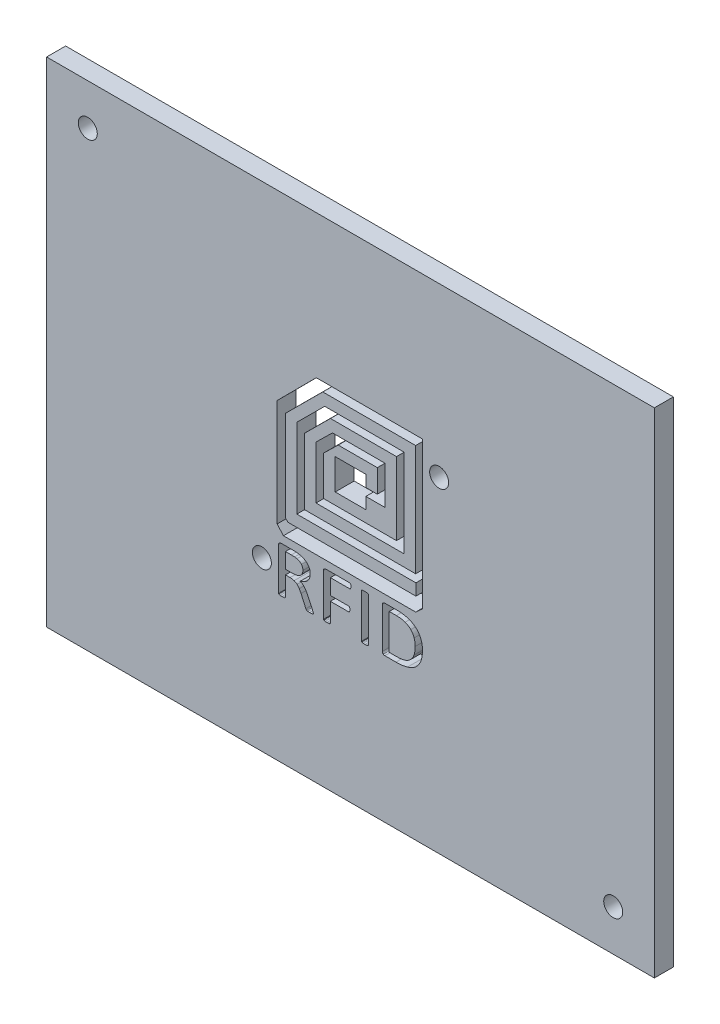
SolidWorks part; units mm, degrees
ref_plane "Alzado" through (0, 0, 0) normal (0, 0, 1) x (1, 0, 0)
ref_plane "Planta" through (0, 0, 0) normal (0, 1, 0) x (1, 0, 0)
ref_plane "Vista lateral" through (0, 0, 0) normal (1, 0, 0) x (0, 0, -1)
sketch "Croquis1" plane through (0, 0, 0) normal (0, 0, 1) x (1, 0, 0)
  line L5 (-48, -39) -> (48, -39)
  line L6 (-48, -39) -> (-48, 39)
  line L19 (-48, 39) -> (48, 39)
  line L24 (48, -39) -> (48, 39)
  line L25 (-48, -39) -> (48, 39) construction
  line L26 (-48, 39) -> (48, -39) construction
  point P0 (0, 0)
  dimension "D1" = 96
  dimension "D2" = 78
extrude "Saliente-Extruir2" add sketch "Croquis1" against normal blind 3
sketch "Croquis2" plane through (0, 0, 0) normal (0, 0, 1) x (1, 0, 0)
  line L0 (0, 39) -> (0, -39) construction
  line L1 (-21.5, 20) -> (21.5, 20) construction
  line L2 (-21.5, 20) -> (-21.5, -20) construction
  line L3 (-21.5, -20) -> (21.5, -20) construction
  line L4 (21.5, 20) -> (21.5, -20) construction
  line L5 (-48, 39) -> (48, 39) construction
  line L6 (0, 20) -> (0, -20) construction
  line L15 (-21.5, 0) -> (21.5, 0) construction
  line L16 (-48, -39) -> (48, -39) construction
  line L17 (-48, 0) -> (48, 0) construction
  line L18 (-48, -39) -> (-48, 39) construction
  line L20 (-48, 39) -> (48, 39)
  line L21 (48, -39) -> (48, 39) construction
  line L22 (-48, 39) -> (-48, -39)
  line L23 (-48, -39) -> (48, -39)
  line L24 (48, 39) -> (48, -39)
  circle A1 centre (-14, -12.5) radius 1.5
  circle A2 centre (14, 12.5) radius 1.5
  circle A5 centre (-41.5, 32.5) radius 1.5
  circle A6 centre (41.5, -32.5) radius 1.5
  point P8 (0, 0)
  dimension "D1" = 7.5
  dimension "D2" = 7.5
  dimension "D8" = 6.5
  dimension "D10" = 6.5
  dimension "D3" = 7.5
  dimension "D4" = 3
  dimension "D7" = 3
  dimension "D11" = 6.5
  dimension "D12" = 6.5
  dimension "D13" = 3
  dimension "D5" = 43
  dimension "D6" = 40
  dimension "D9" = 7.5
extrude "Cortar-Extruir1" cut sketch "Croquis2" against normal through all flip side to cut
sketch "Sketch6" plane through (0, 0, 0) normal (0, 0, 1) x (1, 0, 0)
  line L0 (1.7275, -9.1526) -> (1.7275, -16.0516)
  line L1 (2.8268, -16.0516) -> (2.8268, -9.1526)
  line L2 (2.2798, -8.9746) -> (2.2801, -8.9746)
  line L3 (-11.373, -9.3975) -> (-11.373, -16.0515)
  line L4 (-10.2742, -16.0515) -> (-10.2742, -12.9911)
  line L5 (-10.2742, -12.9911) -> (-9.54, -12.9911)
  line L6 (-7.8119, -14.3075) -> (-7.0556, -15.9986)
  line L7 (-6.0064, -15.6431) -> (-6.7462, -14.0625)
  line L8 (-9.2084, -9.0081) -> (-10.9645, -9.0083)
  line L9 (-4.2786, -9.3975) -> (-4.2786, -16.0515)
  line L10 (-3.1793, -16.0515) -> (-3.1793, -13.0584)
  line L11 (-3.1793, -13.0584) -> (-0.3195, -13.0584)
  line L12 (-0.3195, -12.2597) -> (-3.1793, -12.2597)
  line L13 (-3.1793, -12.2597) -> (-3.1793, -9.8191)
  line L14 (-3.1793, -9.8191) -> (-0.1539, -9.8191)
  line L15 (-0.1539, -9.0062) -> (-3.8702, -9.0083)
  line L16 (5.024, -9.3975) -> (5.024, -15.8065)
  line L17 (5.4325, -16.1957) -> (7.1771, -16.1957)
  line L18 (7.2987, -9.0086) -> (5.4325, -9.0083)
  line L19 (-10.2744, -9.7961) -> (-9.3524, -9.7961)
  line L20 (-9.2031, -12.2181) -> (-10.2742, -12.2181)
  line L21 (-10.2742, -12.2181) -> (-10.2744, -9.7961)
  line L22 (6.1171, -9.8011) -> (7.2378, -9.8011)
  line L23 (7.2489, -15.3934) -> (6.1171, -15.3934)
  line L24 (6.1171, -15.3934) -> (6.1171, -9.8011)
  line L25 (-11.5939, -6.6847) -> (-11.5939, 10.2047)
  line L26 (2.2798, -8.9746) -> (2.5393, -8.9893)
  line L27 (-5.4007, 16.419) -> (11.4061, 16.419)
  line L28 (11.4061, 16.419) -> (11.4061, -6.7899)
  line L29 (11.4061, -6.7899) -> (10.2993, -7.7916)
  line L30 (10.2993, -7.7916) -> (-10.5922, -7.7916)
  line L31 (-10.5922, -7.7916) -> (-11.5939, -6.6847)
  line L32 (10.3297, -3.7737) -> (-8.4737, -3.7737)
  line L33 (-8.4737, -3.7737) -> (-8.4737, 8.8007)
  line L34 (-8.4737, 8.8007) -> (-4.0713, 13.1737)
  line L35 (-4.0713, 13.1737) -> (8.4737, 13.1737)
  line L36 (8.4737, 13.1737) -> (8.4737, -0.7474)
  line L37 (8.4737, -0.7474) -> (-5.4474, -0.7474)
  line L38 (-5.4474, -0.7474) -> (-5.4474, 7.6003)
  line L39 (-2.8521, 10.1474) -> (5.4474, 10.1474)
  line L40 (5.4474, 10.1474) -> (5.4474, 4.0947)
  line L41 (5.4474, 4.0947) -> (2.4211, 4.0947)
  line L42 (2.4211, 4.0947) -> (2.4211, 2.279)
  line L43 (2.4211, 2.279) -> (-2.4211, 2.279)
  line L44 (-2.4211, 2.279) -> (-2.4211, 7.1211)
  line L45 (-2.4211, 7.1211) -> (2.4211, 7.1211)
  line L46 (2.4211, 7.1211) -> (2.4211, 5.3053)
  line L47 (2.4211, 5.3053) -> (4.2369, 5.3053)
  line L48 (4.2369, 5.3053) -> (4.2369, 8.9368)
  line L49 (4.2369, 8.9368) -> (-1.9416, 8.9368)
  line L50 (-4.2368, 6.6956) -> (-4.2368, 0.4632)
  line L51 (-4.2368, 0.4632) -> (7.2632, 0.4632)
  line L52 (7.2632, 0.4632) -> (7.2632, 11.9632)
  line L53 (7.2632, 11.9632) -> (-3.1624, 11.9632)
  line L54 (-7.2631, 7.8939) -> (-7.2631, -2.5632)
  line L55 (-7.2631, -2.5632) -> (10.2895, -2.5632)
  line L56 (10.2895, -2.5632) -> (10.2895, 14.9895)
  line L57 (10.2895, 14.9895) -> (-4.3773, 14.9895)
  line L58 (-10.2895, 9.0995) -> (-10.2895, -5.186)
  line L59 (-10.2895, -5.186) -> (-9.8779, -5.5975)
  line L60 (-9.8779, -5.5975) -> (10.3297, -5.5975)
  line L61 (10.3297, -5.5975) -> (10.3297, -3.7737)
  line L62 (-5.4007, 16.419) -> (-11.5939, 10.2047)
  line L65 (-3.1624, 11.9632) -> (-7.2631, 7.8939)
  spline S0 degree 3 poles (2.2801, -8.9746) (2.1823, -8.9746) (2.093, -8.977) (2.0206, -8.9893) knots 0 0 0 0 1 1 1 1
  spline S1 degree 3 poles (2.0206, -8.9893) (1.9525, -8.9967) (1.8962, -9.009) (1.8496, -9.023) knots 0 0 0 0 1 1 1 1
  spline S2 degree 3 poles (1.8496, -9.023) (1.8069, -9.0353) (1.7769, -9.0538) (1.7557, -9.0759) knots 0 0 0 0 1 1 1 1
  spline S3 degree 3 poles (1.7557, -9.0759) (1.7388, -9.098) (1.7275, -9.1231) (1.7275, -9.1526) knots 0 0 0 0 1 1 1 1
  spline S4 degree 3 poles (1.7275, -16.0516) (1.7275, -16.0811) (1.7388, -16.1062) (1.7557, -16.1284) knots 0 0 0 0 1 1 1 1
  spline S5 degree 3 poles (1.7557, -16.1284) (1.7727, -16.1505) (1.8015, -16.1712) (1.8439, -16.1859) knots 0 0 0 0 1 1 1 1
  spline S6 degree 3 poles (1.8439, -16.1859) (1.8863, -16.1982) (1.9429, -16.2031) (2.0149, -16.2105) knots 0 0 0 0 1 1 1 1
  spline S7 degree 3 poles (2.0149, -16.2105) (2.0873, -16.2228) (2.1778, -16.2302) (2.2798, -16.2302) knots 0 0 0 0 1 1 1 1
  spline S8 degree 3 poles (2.2798, -16.2302) (2.3861, -16.2302) (2.4712, -16.2228) (2.5393, -16.2105) knots 0 0 0 0 1 1 1 1
  spline S9 degree 3 poles (2.5393, -16.2105) (2.6117, -16.2031) (2.6679, -16.1982) (2.7103, -16.1859) knots 0 0 0 0 1 1 1 1
  spline S10 degree 3 poles (2.7103, -16.1859) (2.753, -16.1712) (2.7815, -16.1505) (2.7985, -16.1284) knots 0 0 0 0 1 1 1 1
  spline S11 degree 3 poles (2.7985, -16.1284) (2.8155, -16.1062) (2.8268, -16.0811) (2.8268, -16.0516) knots 0 0 0 0 1 1 1 1
  spline S12 degree 3 poles (2.8268, -9.1526) (2.8268, -9.1231) (2.8155, -9.098) (2.7985, -9.0759) knots 0 0 0 0 1 1 1 1
  spline S13 degree 3 poles (2.7985, -9.0759) (2.7815, -9.0538) (2.7527, -9.0341) (2.7103, -9.023) knots 0 0 0 0 1 1 1 1
  spline S14 degree 3 poles (2.7103, -9.023) (2.6676, -9.0083) (2.6114, -8.9967) (2.5393, -8.9893) knots 0 0 0 0 1 1 1 1
  spline S16 degree 3 poles (-10.9645, -9.0083) (-11.0623, -9.0083) (-11.1567, -9.0356) (-11.2461, -9.0948) knots 0 0 0 0 1 1 1 1
  spline S17 degree 3 poles (-11.2461, -9.0948) (-11.3311, -9.1504) (-11.373, -9.253) (-11.373, -9.3975) knots 0 0 0 0 1 1 1 1
  spline S18 degree 3 poles (-11.373, -16.0515) (-11.373, -16.081) (-11.3673, -16.1061) (-11.3504, -16.1282) knots 0 0 0 0 1 1 1 1
  spline S19 degree 3 poles (-11.3504, -16.1282) (-11.3334, -16.1504) (-11.2992, -16.171) (-11.2565, -16.1858) knots 0 0 0 0 1 1 1 1
  spline S20 degree 3 poles (-11.2565, -16.1858) (-11.2138, -16.1981) (-11.159, -16.203) (-11.0909, -16.2104) knots 0 0 0 0 1 1 1 1
  spline S21 degree 3 poles (-11.0909, -16.2104) (-11.0185, -16.2227) (-10.9323, -16.2301) (-10.826, -16.2301) knots 0 0 0 0 1 1 1 1
  spline S22 degree 3 poles (-10.826, -16.2301) (-10.7197, -16.2301) (-10.629, -16.2227) (-10.5612, -16.2104) knots 0 0 0 0 1 1 1 1
  spline S23 degree 3 poles (-10.5612, -16.2104) (-10.4888, -16.203) (-10.4337, -16.1981) (-10.3955, -16.1858) knots 0 0 0 0 1 1 1 1
  spline S24 degree 3 poles (-10.3955, -16.1858) (-10.3528, -16.171) (-10.3243, -16.1504) (-10.3073, -16.1282) knots 0 0 0 0 1 1 1 1
  spline S25 degree 3 poles (-10.3073, -16.1282) (-10.2847, -16.1061) (-10.2742, -16.081) (-10.2742, -16.0515) knots 0 0 0 0 1 1 1 1
  spline S26 degree 3 poles (-9.54, -12.9911) (-9.2889, -12.9911) (-9.0782, -13.0253) (-8.8995, -13.092) knots 0 0 0 0 1 1 1 1
  spline S27 degree 3 poles (-8.8995, -13.092) (-8.7209, -13.155) (-8.5622, -13.2425) (-8.4303, -13.361) knots 0 0 0 0 1 1 1 1
  spline S28 degree 3 poles (-8.4303, -13.361) (-8.2982, -13.4759) (-8.1872, -13.6161) (-8.0935, -13.779) knots 0 0 0 0 1 1 1 1
  spline S29 degree 3 poles (-8.0935, -13.779) (-7.9957, -13.9382) (-7.9013, -14.1149) (-7.8119, -14.3075) knots 0 0 0 0 1 1 1 1
  spline S30 degree 3 poles (-7.0556, -15.9986) (-7.0386, -16.0431) (-7.016, -16.0795) (-6.9948, -16.1091) knots 0 0 0 0 1 1 1 1
  spline S31 degree 3 poles (-6.9948, -16.1091) (-6.9694, -16.1386) (-6.938, -16.1674) (-6.8953, -16.1858) knots 0 0 0 0 1 1 1 1
  spline S32 degree 3 poles (-6.8953, -16.1858) (-6.8529, -16.2006) (-6.7978, -16.2079) (-6.7297, -16.2146) knots 0 0 0 0 1 1 1 1
  spline S33 degree 3 poles (-6.7297, -16.2146) (-6.6573, -16.222) (-6.5643, -16.2293) (-6.4535, -16.2293) knots 0 0 0 0 1 1 1 1
  spline S34 degree 3 poles (-6.4535, -16.2293) (-6.326, -16.2293) (-6.2209, -16.222) (-6.1444, -16.2146) knots 0 0 0 0 1 1 1 1
  spline S35 degree 3 poles (-6.1444, -16.2146) (-6.0678, -16.2072) (-6.0104, -16.1998) (-5.9677, -16.1858) knots 0 0 0 0 1 1 1 1
  spline S36 degree 3 poles (-5.9677, -16.1858) (-5.9253, -16.171) (-5.8976, -16.1504) (-5.8849, -16.1282) knots 0 0 0 0 1 1 1 1
  spline S37 degree 3 poles (-5.8849, -16.1282) (-5.8707, -16.1061) (-5.8679, -16.081) (-5.8679, -16.0515) knots 0 0 0 0 1 1 1 1
  spline S38 degree 3 poles (-5.8679, -16.0515) (-5.8679, -16.022) (-5.8736, -15.9784) (-5.8905, -15.9265) knots 0 0 0 0 1 1 1 1
  spline S39 degree 3 poles (-5.8905, -15.9265) (-5.9075, -15.8709) (-5.9468, -15.7765) (-6.0064, -15.6431) knots 0 0 0 0 1 1 1 1
  spline S40 degree 3 poles (-6.7462, -14.0625) (-6.8313, -13.8809) (-6.915, -13.7168) (-7.0001, -13.5724) knots 0 0 0 0 1 1 1 1
  spline S41 degree 3 poles (-7.0001, -13.5724) (-7.0851, -13.428) (-7.1781, -13.2992) (-7.2762, -13.1881) knots 0 0 0 0 1 1 1 1
  spline S42 degree 3 poles (-7.2762, -13.1881) (-7.3698, -13.0769) (-7.4693, -12.9825) (-7.5799, -12.9046) knots 0 0 0 0 1 1 1 1
  spline S43 degree 3 poles (-7.5799, -12.9046) (-7.6904, -12.8232) (-7.8193, -12.7595) (-7.9553, -12.7076) knots 0 0 0 0 1 1 1 1
  spline S44 degree 3 poles (-7.9553, -12.7076) (-7.7128, -12.6336) (-7.4885, -12.5411) (-7.2928, -12.4337) knots 0 0 0 0 1 1 1 1
  spline S45 degree 3 poles (-7.2928, -12.4337) (-7.0972, -12.3263) (-6.9308, -12.2035) (-6.7904, -12.059) knots 0 0 0 0 1 1 1 1
  spline S46 degree 3 poles (-6.7904, -12.059) (-6.6499, -11.9109) (-6.5425, -11.7386) (-6.4702, -11.5497) knots 0 0 0 0 1 1 1 1
  spline S47 degree 3 poles (-6.4702, -11.5497) (-6.3936, -11.3571) (-6.3596, -11.1418) (-6.3596, -10.9012) knots 0 0 0 0 1 1 1 1
  spline S48 degree 3 poles (-6.3596, -10.9012) (-6.3596, -10.6531) (-6.4015, -10.4274) (-6.4866, -10.2238) knots 0 0 0 0 1 1 1 1
  spline S49 degree 3 poles (-6.4866, -10.2238) (-6.5674, -10.0164) (-6.6907, -9.8353) (-6.8565, -9.6761) knots 0 0 0 0 1 1 1 1
  spline S50 degree 3 poles (-6.8565, -9.6761) (-7.0224, -9.5169) (-7.228, -9.3858) (-7.4748, -9.2821) knots 0 0 0 0 1 1 1 1
  spline S51 degree 3 poles (-7.4748, -9.2821) (-7.7173, -9.1786) (-7.9949, -9.0996) (-8.314, -9.0516) knots 0 0 0 0 1 1 1 1
  spline S52 degree 3 poles (-8.314, -9.0516) (-8.4245, -9.0393) (-8.5545, -9.0295) (-8.6949, -9.0229) knots 0 0 0 0 1 1 1 1
  spline S53 degree 3 poles (-8.6949, -9.0229) (-8.8312, -9.0106) (-8.9999, -9.0081) (-9.2084, -9.0081) knots 0 0 0 0 1 1 1 1
  spline S54 degree 3 poles (-3.8702, -9.0083) (-3.968, -9.0083) (-4.0624, -9.0356) (-4.1517, -9.0948) knots 0 0 0 0 1 1 1 1
  spline S55 degree 3 poles (-4.1517, -9.0948) (-4.2368, -9.1504) (-4.2786, -9.253) (-4.2786, -9.3975) knots 0 0 0 0 1 1 1 1
  spline S56 degree 3 poles (-4.2786, -16.0515) (-4.2786, -16.0773) (-4.2673, -16.1024) (-4.2504, -16.1282) knots 0 0 0 0 1 1 1 1
  spline S57 degree 3 poles (-4.2504, -16.1282) (-4.2334, -16.1504) (-4.2046, -16.171) (-4.1622, -16.1858) knots 0 0 0 0 1 1 1 1
  spline S58 degree 3 poles (-4.1622, -16.1858) (-4.1198, -16.1981) (-4.0632, -16.203) (-3.9912, -16.2104) knots 0 0 0 0 1 1 1 1
  spline S59 degree 3 poles (-3.9912, -16.2104) (-3.9188, -16.2227) (-3.8283, -16.2301) (-3.7263, -16.2301) knots 0 0 0 0 1 1 1 1
  spline S60 degree 3 poles (-3.7263, -16.2301) (-3.6158, -16.2301) (-3.5293, -16.2227) (-3.4614, -16.2104) knots 0 0 0 0 1 1 1 1
  spline S61 degree 3 poles (-3.4614, -16.2104) (-3.3933, -16.203) (-3.3385, -16.1981) (-3.2958, -16.1858) knots 0 0 0 0 1 1 1 1
  spline S62 degree 3 poles (-3.2958, -16.1858) (-3.2531, -16.171) (-3.2189, -16.1504) (-3.2019, -16.1282) knots 0 0 0 0 1 1 1 1
  spline S63 degree 3 poles (-3.2019, -16.1282) (-3.185, -16.1024) (-3.1793, -16.0773) (-3.1793, -16.0515) knots 0 0 0 0 1 1 1 1
  spline S64 degree 3 poles (-0.3195, -13.0584) (-0.2898, -13.0584) (-0.2621, -13.0485) (-0.2367, -13.0338) knots 0 0 0 0 1 1 1 1
  spline S65 degree 3 poles (-0.2367, -13.0338) (-0.207, -13.0141) (-0.1807, -12.9912) (-0.1592, -12.9617) knots 0 0 0 0 1 1 1 1
  spline S66 degree 3 poles (-0.1592, -12.9617) (-0.1366, -12.9285) (-0.1236, -12.8896) (-0.1151, -12.8417) knots 0 0 0 0 1 1 1 1
  spline S67 degree 3 poles (-0.1151, -12.8417) (-0.1067, -12.7898) (-0.1038, -12.7246) (-0.1038, -12.6542) knots 0 0 0 0 1 1 1 1
  spline S68 degree 3 poles (-0.1038, -12.6542) (-0.1038, -12.5765) (-0.1064, -12.515) (-0.1151, -12.4668) knots 0 0 0 0 1 1 1 1
  spline S69 degree 3 poles (-0.1151, -12.4668) (-0.1236, -12.4149) (-0.1378, -12.3763) (-0.1592, -12.3468) knots 0 0 0 0 1 1 1 1
  spline S70 degree 3 poles (-0.1592, -12.3468) (-0.1819, -12.3172) (-0.2067, -12.2954) (-0.2367, -12.2843) knots 0 0 0 0 1 1 1 1
  spline S71 degree 3 poles (-0.2367, -12.2843) (-0.2621, -12.2695) (-0.2898, -12.2597) (-0.3195, -12.2597) knots 0 0 0 0 1 1 1 1
  spline S72 degree 3 poles (-0.1539, -9.8191) (-0.1242, -9.8191) (-0.0965, -9.8093) (-0.0711, -9.7945) knots 0 0 0 0 1 1 1 1
  spline S73 degree 3 poles (-0.0711, -9.7945) (-0.0414, -9.7798) (-0.0151, -9.7569) (0.0061, -9.7274) knots 0 0 0 0 1 1 1 1
  spline S74 degree 3 poles (0.0061, -9.7274) (0.0287, -9.6942) (0.0417, -9.6543) (0.0502, -9.6024) knots 0 0 0 0 1 1 1 1
  spline S75 degree 3 poles (0.0502, -9.6024) (0.0587, -9.5505) (0.0615, -9.4853) (0.0615, -9.415) knots 0 0 0 0 1 1 1 1
  spline S76 degree 3 poles (0.0615, -9.415) (0.0615, -9.3446) (0.059, -9.2844) (0.0502, -9.2325) knots 0 0 0 0 1 1 1 1
  spline S77 degree 3 poles (0.0502, -9.2325) (0.0417, -9.1769) (0.0276, -9.136) (0.0061, -9.1028) knots 0 0 0 0 1 1 1 1
  spline S78 degree 3 poles (0.0061, -9.1028) (-0.0165, -9.0694) (-0.0414, -9.0455) (-0.0711, -9.0308) knots 0 0 0 0 1 1 1 1
  spline S79 degree 3 poles (-0.0711, -9.0308) (-0.0965, -9.016) (-0.1242, -9.0062) (-0.1539, -9.0062) knots 0 0 0 0 1 1 1 1
  spline S80 degree 3 poles (5.4325, -9.0083) (5.3347, -9.0083) (5.2403, -9.0356) (5.151, -9.0948) knots 0 0 0 0 1 1 1 1
  spline S81 degree 3 poles (5.151, -9.0948) (5.0659, -9.1504) (5.024, -9.253) (5.024, -9.3975) knots 0 0 0 0 1 1 1 1
  spline S82 degree 3 poles (5.024, -15.8065) (5.024, -15.9508) (5.0659, -16.05) (5.151, -16.1091) knots 0 0 0 0 1 1 1 1
  spline S83 degree 3 poles (5.151, -16.1091) (5.2403, -16.1647) (5.3347, -16.1957) (5.4325, -16.1957) knots 0 0 0 0 1 1 1 1
  spline S84 degree 3 poles (7.1771, -16.1957) (7.8834, -16.1957) (8.4939, -16.117) (9.0045, -15.9652) knots 0 0 0 0 1 1 1 1
  spline S85 degree 3 poles (9.0045, -15.9652) (9.5151, -15.8135) (9.9475, -15.5866) (10.2964, -15.283) knots 0 0 0 0 1 1 1 1
  spline S86 degree 3 poles (10.2964, -15.283) (10.6495, -14.9757) (10.914, -14.5928) (11.0969, -14.13) knots 0 0 0 0 1 1 1 1
  spline S87 degree 3 poles (11.0969, -14.13) (11.2798, -13.6635) (11.3731, -13.1186) (11.3731, -12.4965) knots 0 0 0 0 1 1 1 1
  spline S88 degree 3 poles (11.3731, -12.4965) (11.3731, -11.956) (11.288, -11.4703) (11.1136, -11.0408) knots 0 0 0 0 1 1 1 1
  spline S89 degree 3 poles (11.1136, -11.0408) (10.9434, -10.6113) (10.6878, -10.2454) (10.3517, -9.9455) knots 0 0 0 0 1 1 1 1
  spline S90 degree 3 poles (10.3517, -9.9455) (10.0198, -9.6418) (9.6086, -9.4128) (9.1151, -9.2536) knots 0 0 0 0 1 1 1 1
  spline S91 degree 3 poles (9.1151, -9.2536) (8.6215, -9.0908) (8.0135, -9.0086) (7.2987, -9.0086) knots 0 0 0 0 1 1 1 1
  spline S92 degree 3 poles (-9.3524, -9.7961) (-9.1353, -9.7961) (-8.9598, -9.8035) (-8.8279, -9.8158) knots 0 0 0 0 1 1 1 1
  spline S93 degree 3 poles (-8.8279, -9.8158) (-8.6917, -9.8281) (-8.5699, -9.8426) (-8.4636, -9.8687) knots 0 0 0 0 1 1 1 1
  spline S94 degree 3 poles (-8.4636, -9.8687) (-8.1232, -9.9538) (-7.8795, -10.0953) (-7.7348, -10.2915) knots 0 0 0 0 1 1 1 1
  spline S95 degree 3 poles (-7.7348, -10.2915) (-7.5901, -10.4841) (-7.5194, -10.7211) (-7.5194, -11.0025) knots 0 0 0 0 1 1 1 1
  spline S96 degree 3 poles (-7.5194, -11.0025) (-7.5194, -11.1764) (-7.5508, -11.3396) (-7.6186, -11.4878) knots 0 0 0 0 1 1 1 1
  spline S97 degree 3 poles (-7.6186, -11.4878) (-7.6825, -11.6358) (-7.7874, -11.761) (-7.9278, -11.8721) knots 0 0 0 0 1 1 1 1
  spline S98 degree 3 poles (-7.9278, -11.8721) (-8.0683, -11.9793) (-8.2451, -12.0686) (-8.4578, -12.1315) knots 0 0 0 0 1 1 1 1
  spline S99 degree 3 poles (-8.4578, -12.1315) (-8.6664, -12.1908) (-8.9138, -12.2181) (-9.2031, -12.2181) knots 0 0 0 0 1 1 1 1
  spline S100 degree 3 poles (7.2378, -9.8011) (7.808, -9.8011) (8.273, -9.8707) (8.6346, -10.0077) knots 0 0 0 0 1 1 1 1
  spline S101 degree 3 poles (8.6346, -10.0077) (8.9963, -10.1447) (9.295, -10.335) (9.529, -10.5794) knots 0 0 0 0 1 1 1 1
  spline S102 degree 3 poles (9.529, -10.5794) (9.7673, -10.8239) (9.9428, -11.1168) (10.0535, -11.4538) knots 0 0 0 0 1 1 1 1
  spline S103 degree 3 poles (10.0535, -11.4538) (10.164, -11.787) (10.2191, -12.146) (10.2191, -12.5347) knots 0 0 0 0 1 1 1 1
  spline S104 degree 3 poles (10.2191, -12.5347) (10.2191, -13.0235) (10.1547, -13.4487) (10.0314, -13.8079) knots 0 0 0 0 1 1 1 1
  spline S105 degree 3 poles (10.0314, -13.8079) (9.9124, -14.1633) (9.7329, -14.4597) (9.4904, -14.6967) knots 0 0 0 0 1 1 1 1
  spline S106 degree 3 poles (9.4904, -14.6967) (9.2478, -14.9336) (8.9466, -15.1104) (8.585, -15.2252) knots 0 0 0 0 1 1 1 1
  spline S107 degree 3 poles (8.585, -15.2252) (8.2233, -15.34) (7.7765, -15.3934) (7.2489, -15.3934) knots 0 0 0 0 1 1 1 1
  spline S108 degree 3 poles (-5.4474, 7.6003) (-4.5823, 8.4493) (-3.7172, 9.2983) (-2.8521, 10.1474) knots 0 0 0 0 1 1 1 1
  spline S109 degree 3 poles (-1.9416, 8.9368) (-2.7067, 8.1898) (-3.4717, 7.4427) (-4.2368, 6.6956) knots 0 0 0 0 1 1 1 1
  spline S111 degree 2 poles (-4.3773, 14.9895) (-8.3188, 11.0628) (-10.2895, 9.0995) knots 0 0 0 1 1 1
extrude "Cortar-Extruir9" cut sketch "Sketch6" against normal blind 10 contours S52 S53 L8 S16 S17 L3 S18 S19 S20 S21 S22 S23 S24 S25 L4 L5 S26 S27 S28 S29 L6 S30 S31 S32 S33 S34 S35 S36 S37 S38 S39 L7 S40 S41 S42 S43 S44 S45 S46 S47 S48 S49 S50 S51 S98 S99 L20 L21 L19 S92 | S78 S79 L15 S54 S55 L9 S56 S57 S58 S59 S60 S61 S62 S63 L10 L11 S64 S65 S66 S67 S68 S69 S70 S71 L12 L13 L14 S72 S73 S74 S75 S76 S77 | S13 S14 L26 S0 S1 S2 S3 L0 S4 S5 S6 S7 S8 S9 S10 S11 L1 S12 | S90 S91 L18 S80 S81 L16 S82 S83 L17 S84 S85 S86 S87 S88 S89 S106 S107 L23 L24 L22 S100 S101 S102 S103 S104 S105 | L27 L62 L25 L31 L30 L29 L28 S111 L57 L56 L55 L54 L65 L53 L52 L51 L50 S109 L49 L48 L47 L46 L45 L44 L43 L42 L41 L40 L39 S108 L38 L37 L36 L35 L34 L33 L32 L61 L60 L59 L58
